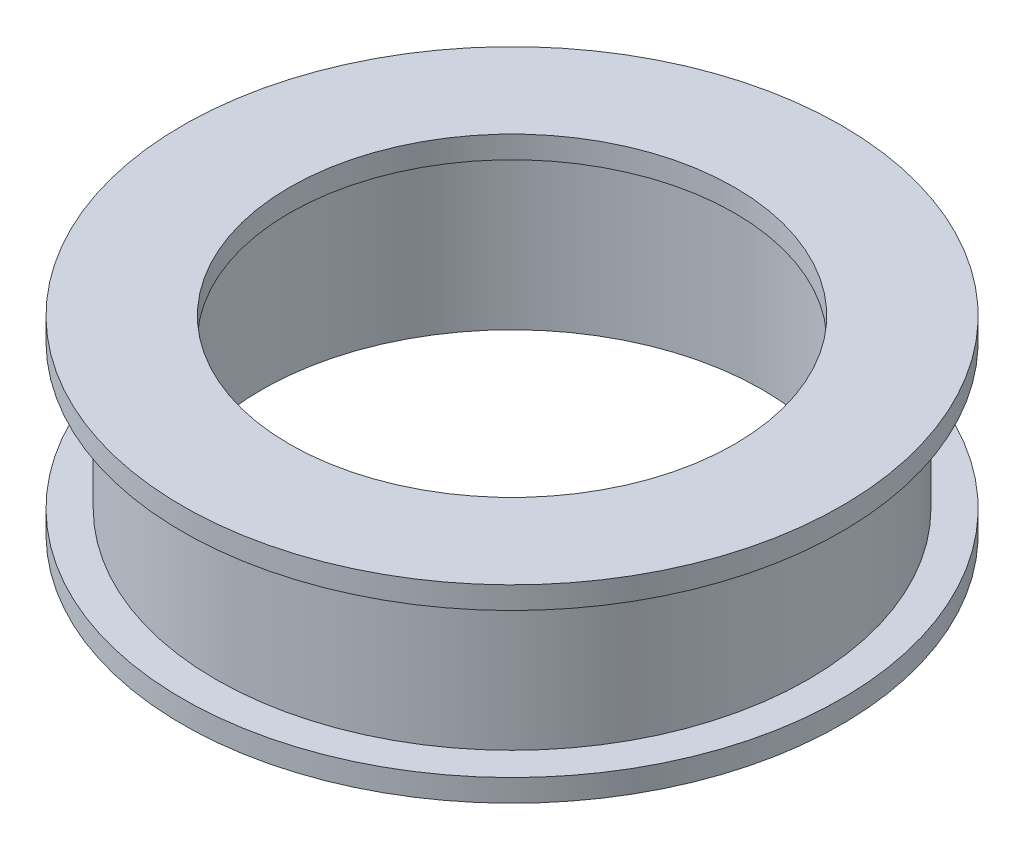
SolidWorks part; units mm, degrees
ref_plane "Front Plane" through (0, 0, 0) normal (0, 0, 1) x (1, 0, 0)
ref_plane "Top Plane" through (0, 0, 0) normal (0, 1, 0) x (1, 0, 0)
ref_plane "Right Plane" through (0, 0, 0) normal (1, 0, 0) x (0, 0, -1)
sketch "Sketch1" plane through (0, 0, 0) normal (0, 0, 1) x (1, 0, 0)
  line L0 (-11.25, 0) -> (-14.8106, 0)
  line L1 (-14.8106, 0) -> (-14.8106, 1)
  line L2 (-14.8106, 1) -> (-13.3106, 1)
  line L3 (-13.3106, 1) -> (-13.3106, 7.5)
  line L4 (-13.3106, 7.5) -> (-14.8106, 7.5)
  line L5 (-14.8106, 7.5) -> (-14.8106, 8.5)
  line L6 (-14.8106, 8.5) -> (-10, 8.5)
  line L7 (-10, 8.5) -> (-10, 7.5)
  line L8 (-10, 7.5) -> (-11.25, 7.5)
  line L9 (-11.25, 7.5) -> (-11.25, 0)
  line L10 (0, 0) -> (0, 7.5) construction
  dimension "D1" = 11.25
  dimension "D2" = 6.5
  dimension "D3" = 1.5
  dimension "D4" = 1.5
  dimension "D5" = 1
  dimension "D6" = 1
  dimension "D7" = 10
revolve "Revolve1" add sketch "Sketch1" angle 360 about L10
